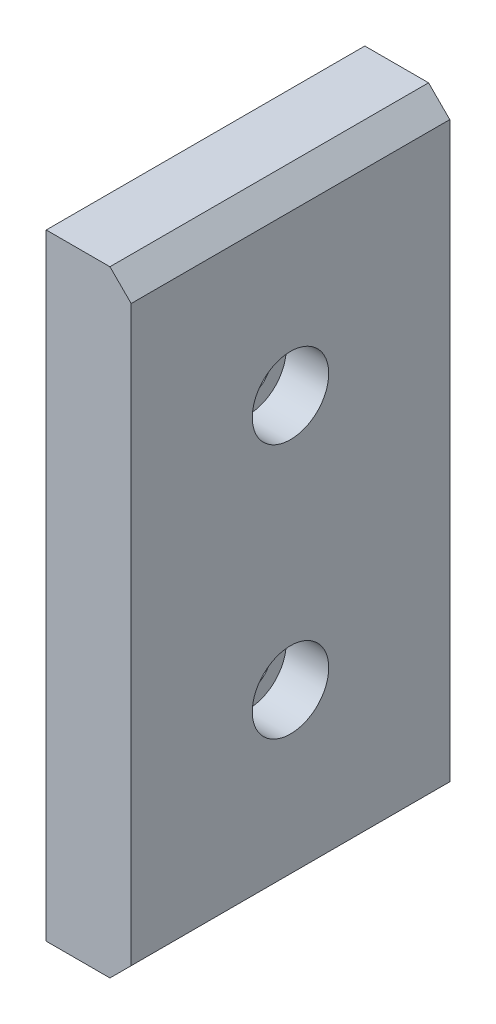
SolidWorks part; units mm, degrees
ref_plane "Спереди" through (0, 0, 0) normal (0, 0, 1) x (1, 0, 0)
ref_plane "Сверху" through (0, 0, 0) normal (0, 1, 0) x (1, 0, 0)
ref_plane "Справа" through (0, 0, 0) normal (1, 0, 0) x (0, 0, -1)
sketch "Эскиз1" plane through (0, 0, 0) normal (1, 0, 0) x (0, 0, -1)
  line L0 (-7.5, 0) -> (7.5, 0) construction
  line L1 (-7.5, 14.5) -> (7.5, 14.5)
  line L2 (-7.5, 14.5) -> (-7.5, -14.5)
  line L3 (-7.5, -14.5) -> (7.5, -14.5)
  line L4 (7.5, 14.5) -> (7.5, -14.5)
  line L5 (-7.5, 14.5) -> (7.5, -14.5) construction
  line L6 (-7.5, -14.5) -> (7.5, 14.5) construction
  circle A0 centre (0, 6) radius 1.1
  circle A1 centre (0, -6) radius 1.1
  point P0 (0, 0)
  dimension "D4" = 2.2
  dimension "D1" = 29
  dimension "D2" = 15
  dimension "D3" = 12
extrude "Бобышка-Вытянуть1" add sketch "Эскиз1" along normal blind 4
sketch "Эскиз2" plane through (4, 0, 0) normal (1, 0, 0) x (0, 0, -1)
  circle A0 centre (0, 6) radius 1.8
  circle A1 centre (0, -6) radius 1.8
  dimension "D1" = 3.6
  dimension "D2" = 3.6
extrude "Вырез-Вытянуть1" cut sketch "Эскиз2" against normal blind 2
chamfer "Фаска1" distance 1 angle 45 2 edges at (4, -14.5, 0) (4, 14.5, 0)
equation "\"motor_diameter\"= 30"
equation "\"mm_diameter\"= IIF ( \"motor_diameter\" < 34 , 41 , \"motor_diameter\" + 8 )"
equation "\"upper_shafts_diameter\"= 5"
equation "\"upper_shats_length\"= 180"
equation "\"upper_bearing_d1\"= 10"
equation "\"upper_bearing_d2\"= 5"
equation "\"upper_bearing_h\"= 15"
equation "\"lower_shafts_diameter\"= 5"
equation "\"lower_shafts_length\"= 180"
equation "\"lower_bearing_d1\"= 10"
equation "\"lower_bearing_d2\"= 5"
equation "\"lower_bearing_h\"= 15"
equation "\"print_offset\"= 0.2"
equation "\"bh_screws_d\"= 2"
equation "\"bh_screws_h\"= 20"
equation "\"bh_screws_hh_d\"= 3.4"
equation "\"bh_screws_hh_h\"= 2"
equation "\"bh_nut_d\"= 3.8"
equation "\"bh_nut_h\"= 2"
equation "\"motor_screws_d\"= 3"
equation "\"motor_screws_h\"= 16"
equation "\"motor_screws_hh_d\"= 5.5"
equation "\"motor_screws_hh_h\"= 3"
equation "\"plate_hole_distance\"= 25.4"
equation "\"plate_screws_d\"= 6.5"
equation "\"shafts_diameter\"= IIF ( \"mm_diameter\" < 42 , 42 + 8 , \"mm_diameter\" + 8 )"
equation "\"central_hole_diameter\"= 8"
equation "\"bh_thikness\"= 4"
equation "\"ends_screws_d\"= 4"
equation "\"ends_screws_h\"= 16"
equation "\"ends_screws_hh_d\"= 6.7"
equation "\"ends_screws_hh_h\"= 4.1"
equation "\"ends_nut_d\"= 6.8"
equation "\"ends_nut_h\"= 3"
equation "\"system_radius\" = ( \"shafts_diameter\" + 12 + \"bh_thikness\" / 2 ) / 2"
equation "\"encoder_distance\"= \"system_radius\" + 4"
equation "\"tape_position\"= \"encoder_distance\" - 2 + 3.9 + 1.7 / 2"
equation "\"D1@Эскиз1\"=\"lower_bearing_h\"+\"bh_thikness\"*2+6"
equation "\"D4@Эскиз1\"=\"bh_screws_d\"+\"print_offset\""
equation "\"D1@Эскиз2\"=\"bh_screws_hh_d\"+\"print_offset\""
equation "\"D2@Эскиз2\"=\"D1@Эскиз2\""
equation "\"D1@Вырез-Вытянуть1\"=\"bh_screws_hh_h\""
